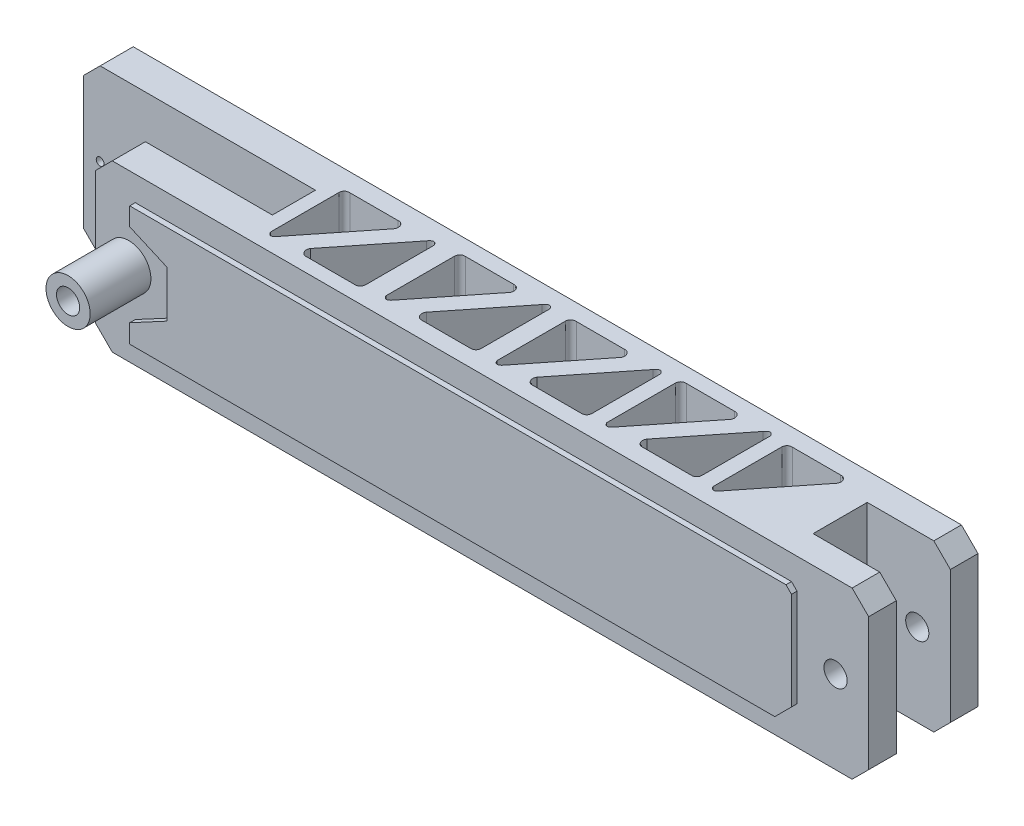
SolidWorks part; units mm, degrees
ref_plane "Plan de face" through (0, 0, 0) normal (0, 0, 1) x (1, 0, 0)
ref_plane "Plan de dessus" through (0, 0, 0) normal (0, 1, 0) x (1, 0, 0)
ref_plane "Plan de droite" through (0, 0, 0) normal (1, 0, 0) x (0, 0, -1)
sketch "Esquisse2" plane through (0, 0, 0) normal (0, 1, 0) x (1, 0, 0)
  line L0 (-70, 9.9) -> (70, 9.9)
  line L1 (0, -11) -> (0, 11) construction
  line L2 (-70, 9.9) -> (-70, -9.9)
  line L3 (-16.5, 0) -> (16.5, 0) construction
  line L4 (70, 9.9) -> (70, -9.9)
  line L5 (-70, -9.9) -> (70, -9.9)
  point P5 (0, -9.9)
  point P9 (0, 9.9)
  point P10 (70, 0)
  point P11 (-70, 0)
  dimension "D1" = 140
  dimension "D2" = 19.8
extrude "Boss.-Extru.1" add sketch "Esquisse2" along normal blind 30
sketch "Esquisse3" plane through (0, 30, 0) normal (0, 1, 0) x (1, 0, 0)
  line L5 (70, 4.9) -> (54.9376, 4.9)
  line L6 (-70, -3.9) -> (-44, -3.9)
  line L7 (-70, 9.9) -> (-70, -9.9) construction
  line L8 (-44, -3.9) -> (-44, 3.9)
  line L9 (-44, 3.9) -> (-70, 3.9)
  line L10 (-70, 3.9) -> (-70, -3.9)
  line L11 (-70, -9.9) -> (70, -9.9) construction
  line L12 (70, 9.9) -> (-70, 9.9) construction
  line L13 (54.9376, 4.9) -> (54.9376, 0)
  line L15 (70, 4.9) -> (70, 0)
  line L16 (70, -9.9) -> (70, 9.9) construction
  line L17 (70, 0) -> (70, -4.9)
  line L18 (70, -4.9) -> (54.9376, -4.9)
  line L19 (54.9376, -4.9) -> (54.9376, 0)
  dimension "D1" = 5
  dimension "D2" = 5
  dimension "D3" = 26
  dimension "D4" = 6
  dimension "D5" = 6
  dimension "D6" = 15.0624
extrude "Enlèv. mat.-Extru.1" cut sketch "Esquisse3" against normal blind 52
sketch "Esquisse4" plane through (0, 0, 9.9) normal (0, 0, 1) x (1, 0, 0)
  line L0 (-70, 30) -> (70, 30) construction
  line L1 (-70, 0) -> (70, 0) construction
  line L2 (70, 30) -> (70, 0) construction
  line L3 (-70, 30) -> (-70, 0) construction
  circle A0 centre (64, 15) radius 2.1
  circle A1 centre (-64, 15) radius 2.1
  point P12 (-70, 15)
  dimension "D4" = 4.2
  dimension "D6" = 4.2
  dimension "D1" = 15
  dimension "D2" = 15
  dimension "D3" = 6
  dimension "D5" = 6
  dimension "D7" = 15
  dimension "D8" = 15
  dimension "D9" = 15
extrude "Enlèv. mat.-Extru.2" cut sketch "Esquisse4" against normal blind 97 and the other way blind 80
sketch "Esquisse5" plane through (0, 0, -9.9) normal (0, 0, -1) x (-1, 0, 0)
  line L0 (45, 13.443) -> (60.1006, 11.25)
  line L1 (45, 16.557) -> (60.1, 18.7494)
  line L2 (67.8989, 11.2494) -> (83, 13.357)
  line L3 (67.9, 18.7494) -> (83, 16.557)
  circle A0 centre (64, 15) radius 5.41 construction
  circle A1 centre (83, 14.957) radius 1.6 construction
  circle A2 centre (45, 15) radius 1.557 construction
  spline S0 degree 3 poles (83, 13.357) (83.8874, 13.3043) (85.3181, 14.9537) (83.8765, 16.616) (83, 16.557) knots 0 0 0 0 0.500032 1 1 1 1
  spline S1 degree 3 poles (60.1006, 11.25) (62.0378, 9.067) (65.9617, 9.0814) (67.8989, 11.2494) knots 0 0 0 0 1 1 1 1
  spline S2 degree 3 poles (60.1, 18.7494) (62.046, 20.9304) (65.954, 20.9314) (67.9, 18.7494) knots 0 0 0 0 1 1 1 1
  spline S3 degree 3 poles (45, 13.443) (44.1476, 13.3868) (42.7385, 15.0001) (44.1473, 16.613) (45, 16.557) knots 0 0 0 0 0.499994 1 1 1 1
  point P3 (67.8989, 11.2494)
  point P4 (67.9, 18.7494)
  point P5 (83, 16.557)
  point P6 (83, 13.357)
  point P9 (83, 14.957)
  point P15 (60.1, 18.7494)
  point P17 (60.1006, 11.25)
  point P18 (45, 16.557)
  point P20 (45, 13.357)
  dimension "D1" = 3.9
  dimension "D5" = 3.9
  dimension "D2" = 15.1
  dimension "D3" = 3.2
  dimension "D4" = 7.5
  dimension "D6" = 15.1
sketch "Esquisse6" plane through (-70, 0, 0) normal (-1, 0, 0) x (0, 0, 1)
  line L0 (-9.9, 0) -> (-9.9, 30)
  line L1 (-9.9, 30) -> (-3.9, 30)
  line L2 (-3.9, 30) -> (-3.9, 0)
  line L3 (-3.9, 0) -> (-9.9, 0)
extrude "Boss.-Extru.2" add sketch "Esquisse6" along normal blind 16
extrude "Enlèv. mat.-Extru.3" cut sketch "Esquisse5" against normal blind 2.5
sketch "Esquisse7" plane through (0, 0, -7.4) normal (0, 0, -1) x (-1, 0, 0)
  circle A0 centre (45.002, 14.9871) radius 0.7
  circle A1 centre (83, 14.9871) radius 0.7
extrude "Enlèv. mat.-Extru.4" cut sketch "Esquisse7" against normal blind 6
sketch "Esquisse8" plane through (0, 30, 0) normal (0, 1, 0) x (1, 0, 0)
  line L6 (-41.5123, 5.707) -> (-41.5123, -6.7477)
  line L7 (-31.7757, 6.6151) -> (-40.4552, 6.6151)
  line L8 (-30.8407, 4.9486) -> (-40.133, -6.7477)
  line L9 (-24.6158, -6.4347) -> (-24.6158, 6.02)
  line L10 (-34.3525, -7.3428) -> (-25.6729, -7.3428)
  line L11 (-35.2874, -5.6763) -> (-25.9952, 6.02)
  line L12 (-21.0552, 6.1851) -> (-21.0552, -6.2696)
  line L13 (-11.3186, 7.0932) -> (-19.9981, 7.0932)
  line L14 (-10.3836, 5.4267) -> (-19.6759, -6.2696)
  line L15 (-4.1587, -5.9566) -> (-4.1587, 6.4981)
  line L16 (-13.8954, -6.8647) -> (-5.2158, -6.8647)
  line L17 (-14.8303, -5.1982) -> (-5.5381, 6.4981)
  line L18 (-0.8249, 6.0232) -> (-0.8249, -6.4314)
  line L19 (8.9118, 6.9314) -> (0.2322, 6.9314)
  line L20 (9.8467, 5.2648) -> (0.5545, -6.4314)
  line L21 (16.0716, -6.1184) -> (16.0716, 6.3363)
  line L22 (6.335, -7.0265) -> (15.0145, -7.0265)
  line L23 (5.4, -5.36) -> (14.6923, 6.3363)
  line L24 (18.845, 6.2682) -> (18.845, -6.1865)
  line L25 (28.5816, 7.1763) -> (19.902, 7.1763)
  line L26 (29.5165, 5.5098) -> (20.2243, -6.1865)
  line L27 (35.7414, -5.8735) -> (35.7414, 6.5812)
  line L28 (26.0048, -6.7816) -> (34.6844, -6.7816)
  line L29 (25.0699, -5.1151) -> (34.3621, 6.5812)
  line L30 (38.4963, 5.8747) -> (38.4963, -6.5799)
  line L31 (48.233, 6.7829) -> (39.5534, 6.7829)
  line L32 (49.1679, 5.1163) -> (39.8757, -6.5799)
  spline S0 degree 3 poles (49.1679, 5.1163) (49.6691, 5.7817) (49.111, 6.9109) (48.233, 6.7829) knots 0 0 0 0 1 1 1 1
  spline S1 degree 2 poles (39.5534, 6.7829) (38.5966, 6.8041) (38.4963, 5.8747) knots 0 0 0 1 1 1
  spline S2 degree 2 poles (39.8757, -6.5799) (39.0557, -7.6767) (38.4963, -6.5799) knots 0 0 0 1 1 1
  spline S6 degree 3 poles (-30.8407, 4.9486) (-30.3395, 5.6139) (-30.8977, 6.7432) (-31.7757, 6.6151) knots 0 0 0 0 1 1 1 1
  spline S7 degree 2 poles (-40.4552, 6.6151) (-41.4121, 6.6363) (-41.5123, 5.707) knots 0 0 0 1 1 1
  spline S8 degree 2 poles (-40.133, -6.7477) (-40.9529, -7.8445) (-41.5123, -6.7477) knots 0 0 0 1 1 1
  spline S9 degree 3 poles (-35.2874, -5.6763) (-35.7886, -6.3416) (-35.2305, -7.4708) (-34.3525, -7.3428) knots 0 0 0 0 1 1 1 1
  spline S10 degree 2 poles (-25.6729, -7.3428) (-24.7161, -7.364) (-24.6158, -6.4347) knots 0 0 0 1 1 1
  spline S11 degree 2 poles (-25.9952, 6.02) (-25.1752, 7.1168) (-24.6158, 6.02) knots 0 0 0 1 1 1
  spline S12 degree 3 poles (-10.3836, 5.4267) (-9.8824, 6.092) (-10.4406, 7.2212) (-11.3186, 7.0932) knots 0 0 0 0 1 1 1 1
  spline S13 degree 2 poles (-19.9981, 7.0932) (-20.955, 7.1144) (-21.0552, 6.1851) knots 0 0 0 1 1 1
  spline S14 degree 2 poles (-19.6759, -6.2696) (-20.4958, -7.3664) (-21.0552, -6.2696) knots 0 0 0 1 1 1
  spline S15 degree 3 poles (-14.8303, -5.1982) (-15.3315, -5.8635) (-14.7734, -6.9928) (-13.8954, -6.8647) knots 0 0 0 0 1 1 1 1
  spline S16 degree 2 poles (-5.2158, -6.8647) (-4.259, -6.8859) (-4.1587, -5.9566) knots 0 0 0 1 1 1
  spline S17 degree 2 poles (-5.5381, 6.4981) (-4.7181, 7.5949) (-4.1587, 6.4981) knots 0 0 0 1 1 1
  spline S18 degree 3 poles (9.8467, 5.2648) (10.3479, 5.9302) (9.7898, 7.0594) (8.9118, 6.9314) knots 0 0 0 0 1 1 1 1
  spline S19 degree 2 poles (0.2322, 6.9314) (-0.7246, 6.9526) (-0.8249, 6.0232) knots 0 0 0 1 1 1
  spline S20 degree 2 poles (0.5545, -6.4314) (-0.2655, -7.5282) (-0.8249, -6.4314) knots 0 0 0 1 1 1
  spline S21 degree 3 poles (5.4, -5.36) (4.8988, -6.0254) (5.457, -7.1546) (6.335, -7.0265) knots 0 0 0 0 1 1 1 1
  spline S22 degree 2 poles (15.0145, -7.0265) (15.9714, -7.0477) (16.0716, -6.1184) knots 0 0 0 1 1 1
  spline S23 degree 2 poles (14.6923, 6.3363) (15.5122, 7.4331) (16.0716, 6.3363) knots 0 0 0 1 1 1
  spline S24 degree 3 poles (29.5165, 5.5098) (30.0178, 6.1751) (29.4596, 7.3043) (28.5816, 7.1763) knots 0 0 0 0 1 1 1 1
  spline S25 degree 2 poles (19.902, 7.1763) (18.9452, 7.1975) (18.845, 6.2682) knots 0 0 0 1 1 1
  spline S26 degree 2 poles (20.2243, -6.1865) (19.4044, -7.2833) (18.845, -6.1865) knots 0 0 0 1 1 1
  spline S27 degree 3 poles (25.0699, -5.1151) (24.5686, -5.7804) (25.1268, -6.9096) (26.0048, -6.7816) knots 0 0 0 0 1 1 1 1
  spline S28 degree 2 poles (34.6844, -6.7816) (35.6412, -6.8028) (35.7414, -5.8735) knots 0 0 0 1 1 1
  spline S29 degree 2 poles (34.3621, 6.5812) (35.182, 7.678) (35.7414, 6.5812) knots 0 0 0 1 1 1
extrude "Enlèv. mat.-Extru.5" cut sketch "Esquisse8" against normal blind 40
sketch "Esquisse9" plane through (0, 0, 9.9) normal (0, 0, 1) x (1, 0, 0)
  circle A0 centre (-64, 15) radius 2.1
  circle A1 centre (-64, 15) radius 4
  dimension "D1" = 8
extrude "Boss.-Extru.3" add sketch "Esquisse9" along normal blind 11
chamfer "Chanfrein1" distance 3 angle 45 8 edges at (-70, 0, 6.9) (-86, 0, -6.9) (-70, 30, 6.9) (-86, 30, -6.9) (70, 0, 7.4) (70, 0, -7.4) (70, 30, 7.4) (70, 30, -7.4)
sketch "Esquisse10" plane through (0, 0, -9.9) normal (0, 0, -1) x (-1, 0, 0)
  line L0 (37.2215, 6.4465) -> (34.5786, 3.8037)
  line L1 (34.5786, 3.8037) -> (-55.9959, 3.8037)
  line L2 (-55.9959, 3.8037) -> (-57.943, 5.7508)
  line L3 (-57.943, 5.7508) -> (-57.943, 24.1516)
  line L4 (-57.943, 24.1516) -> (-54.3883, 27.7064)
  line L5 (-54.3883, 27.7064) -> (34.3638, 26.7049)
  line L6 (34.3638, 26.7049) -> (37.2215, 23.9448)
  line L7 (37.2215, 23.9448) -> (37.2215, 6.4465)
extrude "Boss.-Extru.4" add sketch "Esquisse10" along normal blind 1
sketch "Esquisse11" plane through (0, 0, 9.9) normal (0, 0, 1) x (1, 0, 0)
  line L0 (-62.8358, 25.5223) -> (56.0227, 25.5223)
  line L1 (56.0227, 25.5223) -> (57.0224, 24.5226)
  line L2 (57.0224, 24.5226) -> (57.0224, 6.8503)
  line L3 (57.0224, 6.8503) -> (53.9945, 3.8224)
  line L4 (53.9945, 3.8224) -> (-62.8358, 3.8224)
  line L5 (-62.8358, 3.8224) -> (-62.8358, 7.1924)
  line L6 (-62.8358, 7.1924) -> (-56.0956, 10.8091)
  line L7 (-56.0956, 10.8091) -> (-56.0956, 19.2754)
  line L8 (-56.0956, 19.2754) -> (-62.8358, 22.2345)
  line L9 (-62.8358, 22.2345) -> (-62.8358, 25.5223)
extrude "Boss.-Extru.5" add sketch "Esquisse11" along normal blind 1
